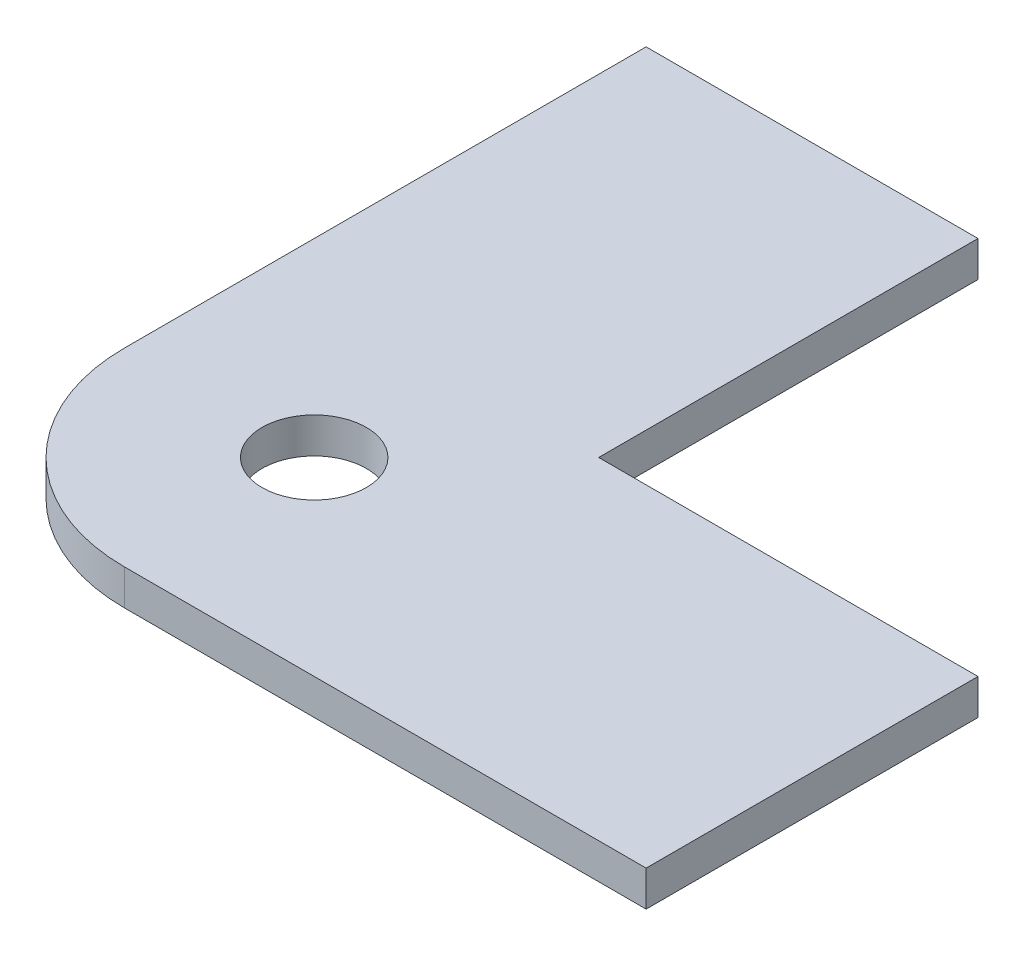
SolidWorks part; units mm, degrees
ref_plane "Front Plane" through (0, 0, 0) normal (0, 0, 1) x (1, 0, 0)
ref_plane "Top Plane" through (0, 0, 0) normal (0, 1, 0) x (1, 0, 0)
ref_plane "Right Plane" through (0, 0, 0) normal (1, 0, 0) x (0, 0, -1)
sketch "Sketch1" plane through (0, 0, 0) normal (0, 1, 0) x (1, 0, 0)
  line L0 (0, 0) -> (0, 11)
  line L1 (0, 0) -> (11, 0)
  line L2 (11, 0) -> (11, 3)
  line L3 (0, 11) -> (3, 11)
  line L4 (-3.9997, 0) -> (-3.9997, 11)
  line L5 (-3.9997, 11) -> (0, 11)
  line L6 (0, -3.9997) -> (11, -3.9997)
  line L7 (11, -3.9997) -> (11, 0)
  line L8 (3, 11) -> (3, 3)
  line L9 (3, 3) -> (11, 3)
  circle A0 centre (0, 0) radius 1.1
  arc A1 (0, -3.9997) -> (-3.9997, 0) centre (0, 0) cw
extrude "Boss-Extrude1" add sketch "Sketch1" along normal blind 0.75 contours A0 L1 L2 L9 L8 L3 L0 | A1 L6 L7 L1 A0 L0 L5 L4
sketch "Sketch2" plane through (0, 0.75, 0) normal (0, 1, 0) x (1, 0, 0)
  circle A0 centre (0, 0) radius 1.1
  circle A1 centre (0, 0) radius 1.55
